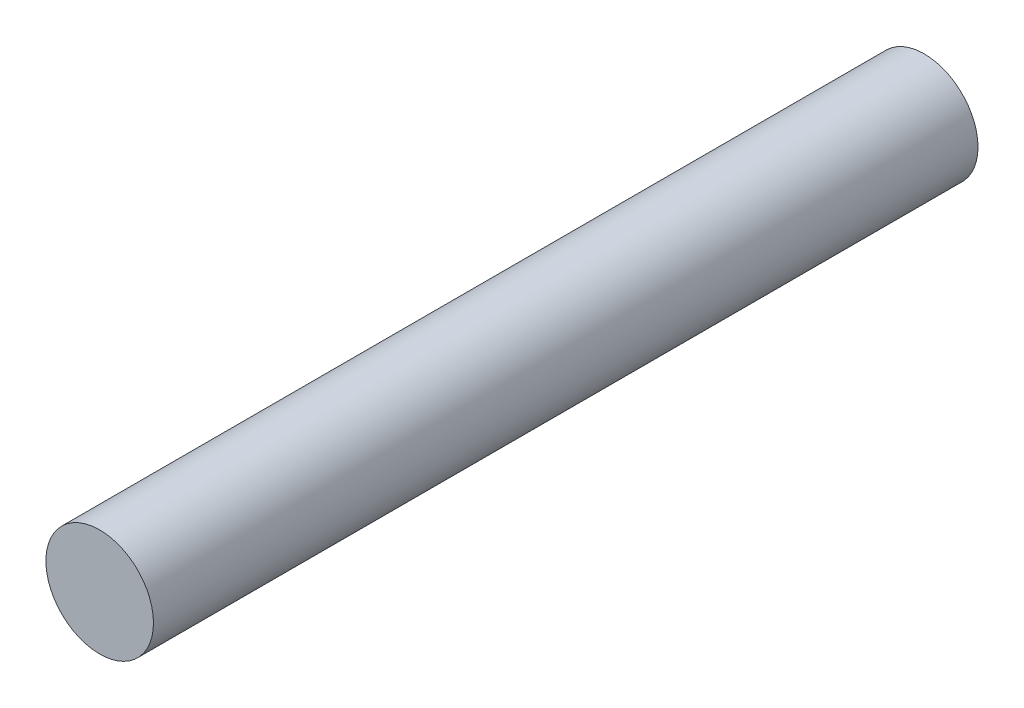
SolidWorks part; units mm, degrees
ref_plane "Front Plane" through (0, 0, 0) normal (0, 0, 1) x (1, 0, 0)
ref_plane "Top Plane" through (0, 0, 0) normal (0, 1, 0) x (1, 0, 0)
ref_plane "Right Plane" through (0, 0, 0) normal (1, 0, 0) x (0, 0, -1)
sketch "Sketch1" plane through (0, 0, 0) normal (0, 0, 1) x (1, 0, 0)
  circle A0 centre (0, 0) radius 1.5
  dimension "D1" = 3
extrude "Boss-Extrude1" add sketch "Sketch1" along normal blind 23
